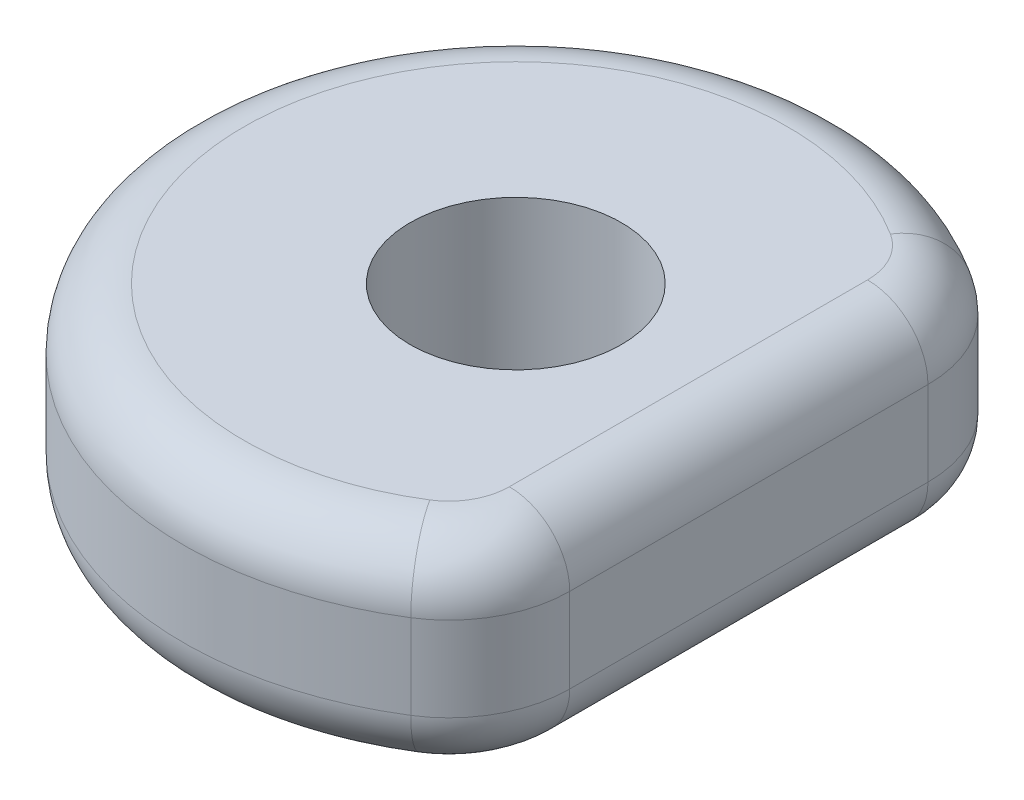
SolidWorks part; units mm, degrees
ref_plane "Alzado" through (0, 0, 0) normal (0, 0, 1) x (1, 0, 0)
ref_plane "Planta" through (0, 0, 0) normal (0, 1, 0) x (1, 0, 0)
ref_plane "Vista lateral" through (0, 0, 0) normal (1, 0, 0) x (0, 0, -1)
sketch "Croquis1" plane through (0, 0, 0) normal (0, 1, 0) x (1, 0, 0)
  line L0 (3.859, 3.919) -> (3.859, -3.919)
  circle A0 centre (0, 0) radius 1.75
  arc A2 (3.859, 3.919) -> (3.859, -3.919) centre (0, 0) ccw
  circle A3 centre (0, 0) radius 5.5 construction
  dimension "D1" = 3.5
  dimension "D2" = 11
extrude "Saliente-Extruir1" add sketch "Croquis1" along normal blind 3.4
fillet "Redondeo1" radius 2 2 edges at (3.859, 1.7, -3.919) (3.859, 1.7, 3.919)
fillet "Redondeo2" radius 1 8 edges at (3.6089, 0, -3.9339) (3.859, 0, 0) (3.6089, 0, 3.9339) (-5.5, 0, 0) (3.6089, 3.4, -3.9339) (3.859, 3.4, 0) (3.6089, 3.4, 3.9339) (-5.5, 3.4, 0)
